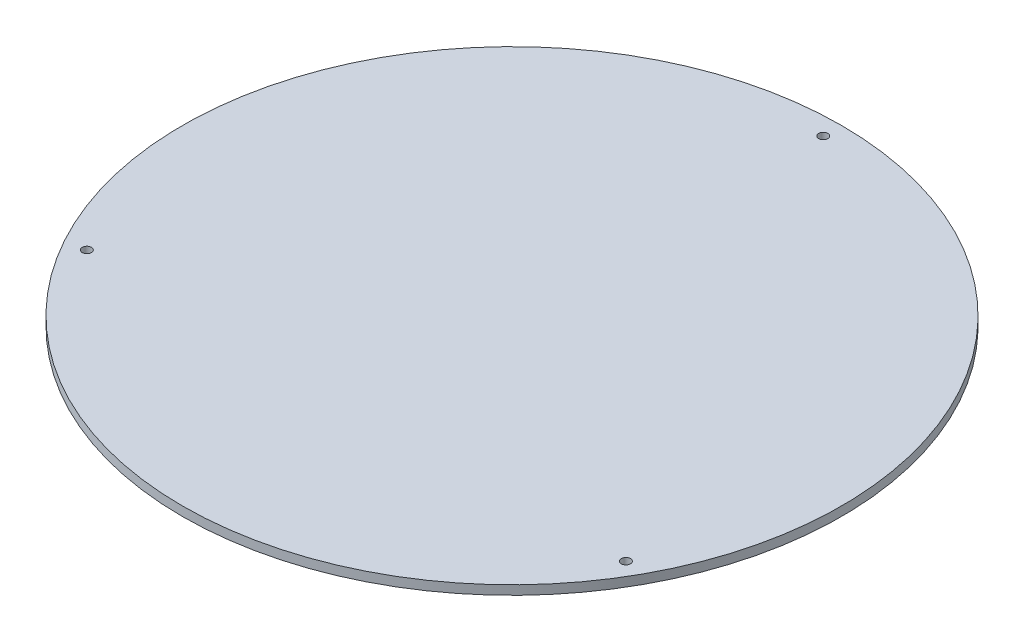
SolidWorks part; units mm, degrees
ref_plane "Front Plane" through (0, 0, 0) normal (0, 0, 1) x (1, 0, 0)
ref_plane "Top Plane" through (0, 0, 0) normal (0, 1, 0) x (1, 0, 0)
ref_plane "Right Plane" through (0, 0, 0) normal (1, 0, 0) x (0, 0, -1)
sketch "Sketch1" plane through (0, 0, 0) normal (0, 1, 0) x (1, 0, 0)
  circle A0 centre (0, 0) radius 228.6
  dimension "D1" = 457.2
extrude "Boss-Extrude1" add sketch "Sketch1" along normal blind 6.35 contours A0
sketch "Sketch2" plane through (0, 6.35, 0) normal (0, 1, 0) x (1, 0, 0)
  line L1 (0, 215.9) -> (-186.9749, -107.95) construction
  line L2 (-186.9749, -107.95) -> (186.9749, -107.95) construction
  line L3 (186.9749, -107.95) -> (0, 215.9) construction
  circle A0 centre (0, 215.9) radius 3.175
  circle A1 centre (0, 0) radius 228.6 construction
  circle A2 centre (0, 0) radius 107.95 construction
  circle A3 centre (-186.9749, -107.95) radius 3.175
  circle A4 centre (186.9749, -107.95) radius 3.175
  dimension "D1" = 6.35
  dimension "D2" = 215.9
  dimension "D3" = 6.35
  dimension "D4" = 6.35
extrude "Cut-Extrude1" cut sketch "Sketch2" against normal through all both and the other way through all
